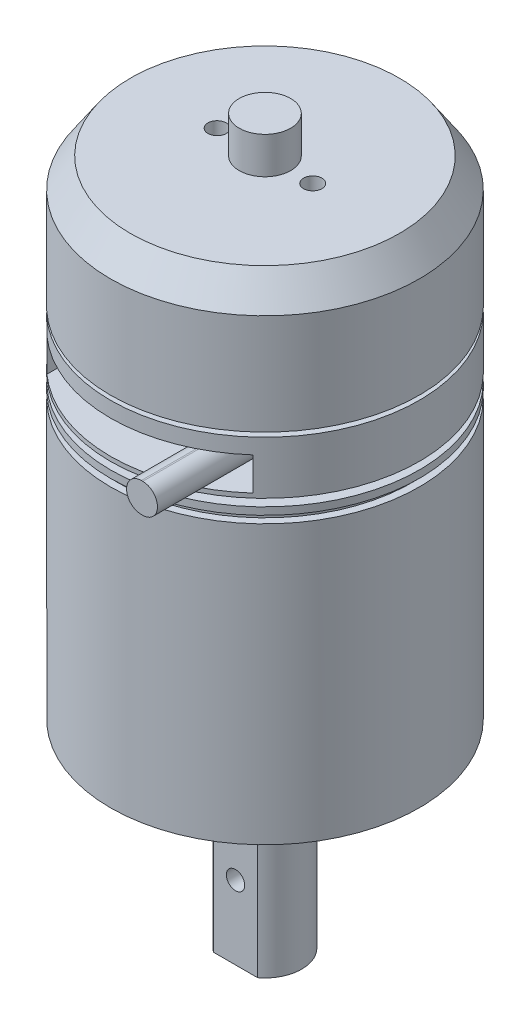
SolidWorks part; units mm, degrees
ref_plane "前视基准面" through (0, 0, 0) normal (0, 0, 1) x (1, 0, 0)
ref_plane "上视基准面" through (0, 0, 0) normal (0, 1, 0) x (1, 0, 0)
ref_plane "右视基准面" through (0, 0, 0) normal (1, 0, 0) x (0, 0, -1)
sketch "草图1" plane through (0, 0, 0) normal (0, 0, 1) x (1, 0, 0)
  line L0 (0, 0) -> (4.1, 0)
  line L1 (4.1, 0) -> (4.1, 6.7)
  line L2 (4.1, 6.7) -> (13.4, 6.7)
  line L3 (13.4, 6.7) -> (13.4, 8.7)
  line L4 (13.4, 8.7) -> (21, 8.7)
  line L5 (21, 8.7) -> (21, 10.2)
  line L6 (21, 10.2) -> (20, 10.2)
  line L7 (20, 10.2) -> (20, 11.2)
  line L8 (20, 11.2) -> (21, 11.2)
  line L9 (21, 11.2) -> (21, 12.2)
  line L10 (21, 12.2) -> (10, 12.2)
  line L11 (10, 12.2) -> (10, 13.2)
  line L12 (10, 13.2) -> (21, 13.2)
  line L13 (21, 13.2) -> (21, 20.4)
  line L14 (21, 20.4) -> (5, 20.4)
  line L15 (5, 20.4) -> (5, 21)
  line L16 (5, 21) -> (21, 21)
  line L17 (21, 21) -> (21, 34.7)
  line L18 (21, 34.7) -> (18.3, 38.7)
  line L19 (18.3, 38.7) -> (3.5, 38.7)
  line L20 (3.5, 38.7) -> (3.5, 43.7)
  line L21 (3.5, 43.7) -> (0, 43.7)
  line L22 (0, 43.7) -> (0, 0) construction
  line L23 (0, 0) -> (0, 43.7)
  dimension "D1" = 8.2
  dimension "D2" = 26.8
  dimension "D3" = 42
  dimension "D4" = 10
  dimension "D5" = 1.5
  dimension "D6" = 1
  dimension "D7" = 1
  dimension "D8" = 20
  dimension "D9" = 1
  dimension "D10" = 7.2
  dimension "D11" = 0.6
  dimension "D12" = 13.7
  dimension "D13" = 5
  dimension "D14" = 2
  dimension "D15" = 6.7
  dimension "D16" = 1
  dimension "D17" = 7
  dimension "D18" = 36.6
  dimension "D19" = 4
  dimension "D20" = 30
revolve "旋转1" add sketch "草图1" angle 360 about L22
ref_plane "基准面1" through (0, 0, 21) normal (0, 0, 1) x (1, 0, 0)
sketch "草图2" plane through (0, 0, 21) normal (0, 0, 1) x (1, 0, 0)
  line L1 (-14, 18.3) -> (14, 18.3)
  line L2 (-14, 18.3) -> (-14, 13.8)
  line L3 (-14, 13.8) -> (14, 13.8)
  line L4 (14, 18.3) -> (14, 13.8)
  line L5 (-14, 18.3) -> (14, 13.8) construction
  line L6 (-14, 13.8) -> (14, 18.3) construction
  line L7 (-21, 13.2) -> (21, 13.2) construction
  point P0 (0, 16.05)
  dimension "D1" = 28
  dimension "D2" = 4.5
  dimension "D3" = 0.6
extrude "切除-拉伸1" cut sketch "草图2" against normal blind 10
sketch "草图3" plane through (0, 0, 11) normal (0, 0, 1) x (1, 0, 0)
  line L0 (9.1851, 16.0532) -> (9.3851, 16.0532) construction
  line L1 (9.1851, 18.0532) -> (9.3851, 18.0532)
  line L2 (9.1851, 14.0532) -> (9.3851, 14.0532)
  arc A0 (9.1851, 18.0532) -> (9.1851, 14.0532) centre (9.1851, 16.0532) ccw
  arc A1 (9.3851, 14.0532) -> (9.3851, 18.0532) centre (9.3851, 16.0532) ccw
  point P2 (9.2851, 16.0532)
  dimension "D1" = 4
  dimension "D2" = 0.2
extrude "凸台-拉伸1" add sketch "草图3" along normal blind 15
hole_wizard "M3 螺纹孔1" positions "草图5" profile "草图6" tap size "M3" standard "GB"
sketch "草图5" plane through (0, 38.7, 0) normal (0, 1, 0) x (1, 0, 0)
  line L0 (0, 0) -> (0, 8.0606) construction
  point P0 (-6.5, 0)
  point P2 (6.5, 0)
  dimension "D1" = 13
sketch "草图6" plane through (-6.5, 38.7, 0) normal (1, 0, 0) x (0, 0, 1)
  line L0 (0, 0) -> (0, 4.7511)
  line L1 (0, 4.7511) -> (1.25, 4)
  line L2 (1.25, 4) -> (1.25, 0)
  line L5 (1.25, 0) -> (0, 0)
  line L10 (0, 4.7511) -> (-1.25, 4) construction
  line L11 (0, -6.35) -> (0, 107.95) construction
  dimension "螺纹孔钻头直径" = 2.5
  dimension "螺纹孔钻头深度" = 4
  dimension "导头角度" = 118
cosmetic thread "孔螺蚊线1" parameters "D1"=4, "D2"=3
cosmetic thread "孔螺蚊线2" parameters "D1"=4, "D2"=3
sketch "草图7" plane through (0, 0, 0) normal (0, 0, 1) x (1, 0, 0)
  line L0 (0, 8.7) -> (0, -54.6) construction
  line L1 (-13.4, 8.7) -> (13.4, 8.7) construction
  line L2 (0, -54.6) -> (5, -54.6)
  line L3 (5, -54.6) -> (5, -30.5)
  line L4 (5, -30.5) -> (8.275, -30.5)
  line L5 (13, -29.6) -> (13, -27.6)
  line L6 (13, -27.6) -> (21, -27.6)
  line L7 (21, -27.6) -> (21, 8.7)
  line L8 (-21, 8.7) -> (21, 8.7) construction
  line L9 (21, 8.7) -> (0, 8.7)
  line L10 (18.3, 38.7) -> (-18.3, 38.7) construction
  line L11 (13, -29.6) -> (8.275, -29.6)
  line L12 (8.275, -29.6) -> (8.275, -30.5)
  line L13 (0, 8.7) -> (0, -54.6)
  dimension "D1" = 66.3
  dimension "D2" = 2
  dimension "D3" = 0.9
  dimension "D4" = 27
  dimension "D5" = 26
  dimension "D6" = 10
  dimension "D7" = 16.55
revolve "旋转2" add sketch "草图7" angle 360 about L0
sketch "草图8" plane through (0, -54.6, 0) normal (0, -1, 0) x (1, 0, 0)
  line L0 (-3, 4) -> (3, 4)
  circle A0 centre (0, 0) radius 5 construction
  circle A1 centre (0, 0) radius 5 construction
  arc A2 (3, 4) -> (-3, 4) centre (0, 0) ccw
  dimension "D1" = 4
extrude "切除-拉伸2" cut sketch "草图8" against normal blind 20
hole_wizard "M4 螺纹孔1" positions "草图10" profile "草图9" tap size "M4" standard "GB"
sketch "草图10" plane through (0, -27.6, 0) normal (0, -1, 0) x (-1, 0, 0)
  circle A0 centre (0, 0) radius 17.5
  point P5 (0, -17.5)
  point P7 (-17.5, 0)
  point P9 (0, 17.5)
  point P11 (17.5, 0)
  dimension "D1" = 35
sketch "草图9" plane through (-17.5, -27.6, 0) normal (1, 0, 0) x (0, 0, -1)
  line L0 (0, 0) -> (0, 11.0914)
  line L1 (0, 11.0914) -> (1.65, 10.1)
  line L2 (1.65, 10.1) -> (1.65, 0)
  line L5 (1.65, 0) -> (0, 0)
  line L10 (0, 11.0914) -> (-1.65, 10.1) construction
  line L11 (0, -6.35) -> (0, 107.95) construction
  dimension "螺纹孔钻头直径" = 3.3
  dimension "螺纹孔钻头深度" = 10.1
  dimension "导头角度" = 118
cosmetic thread "孔螺蚊线3" parameters "D1"=8, "D2"=4
cosmetic thread "孔螺蚊线4" parameters "D1"=8, "D2"=4
cosmetic thread "孔螺蚊线5" parameters "D1"=8, "D2"=4
cosmetic thread "孔螺蚊线6" parameters "D1"=8, "D2"=4
sketch "草图11" plane through (0, 0, 4) normal (0, 0, 1) x (1, 0, 0)
  line L0 (0, -54.6) -> (0, -36.079) construction
  line L1 (-3, -54.6) -> (3, -54.6) construction
  line L2 (-13.929, -44.6) -> (10.5915, -44.6) construction
  circle A0 centre (0, -44.6) radius 1.9071
  dimension "D1" = 10
hole_wizard "M3 螺纹孔2" positions "3D草图1" profile "草图12" tap size "M3" standard "GB" end condition through all
sketch3d "3D草图1"
  point P0 (0, -44.6, 4)
sketch "草图12" plane through (0, -44.6, 4) normal (1, 0, 0) x (0, -1, 0)
  line L0 (0, 0) -> (0, 25)
  line L1 (0, 25) -> (1.25, 25)
  line L2 (1.25, 25) -> (1.25, 0)
  line L5 (1.25, 0) -> (0, 0)
  line L11 (0, -6.35) -> (0, 107.95) construction
  dimension "螺纹线主直径" = 2.5
  dimension "通孔螺纹孔钻头深度" = 25
sketch "草图15" plane through (0, -54.6, 0) normal (0, -1, 0) x (1, 0, 0)
  point P0 (0, 0)
hole_wizard "M5 螺纹孔1" positions "3D草图5" profile "草图16" tap size "M5" standard "GB"
sketch3d "3D草图5"
  point P0 (0, -54.6, 0)
  point P3 (0, -54.6, 0)
sketch "草图16" plane through (0, -54.6, 0) normal (1, 0, 0) x (0, 0, -1)
  line L0 (0, 0) -> (0, 15.2618)
  line L1 (0, 15.2618) -> (2.1, 14)
  line L2 (2.1, 14) -> (2.1, 0)
  line L5 (2.1, 0) -> (0, 0)
  line L10 (0, 15.2618) -> (-2.1, 14) construction
  line L11 (0, -6.35) -> (0, 107.95) construction
  dimension "螺纹孔钻头直径" = 4.2
  dimension "螺纹孔钻头深度" = 14
  dimension "导头角度" = 118
cosmetic thread "孔螺蚊线8" parameters "D1"=10, "D2"=5
scale "缩放比例1" bodies to scale 117 scale about origin uniform scaling yes scale factor 0.8
scale "缩放比例2" bodies to scale 118 scale about origin uniform scaling yes scale factor 0.8
scale "缩放比例3" scale about origin uniform scaling yes scale factor 0.8
